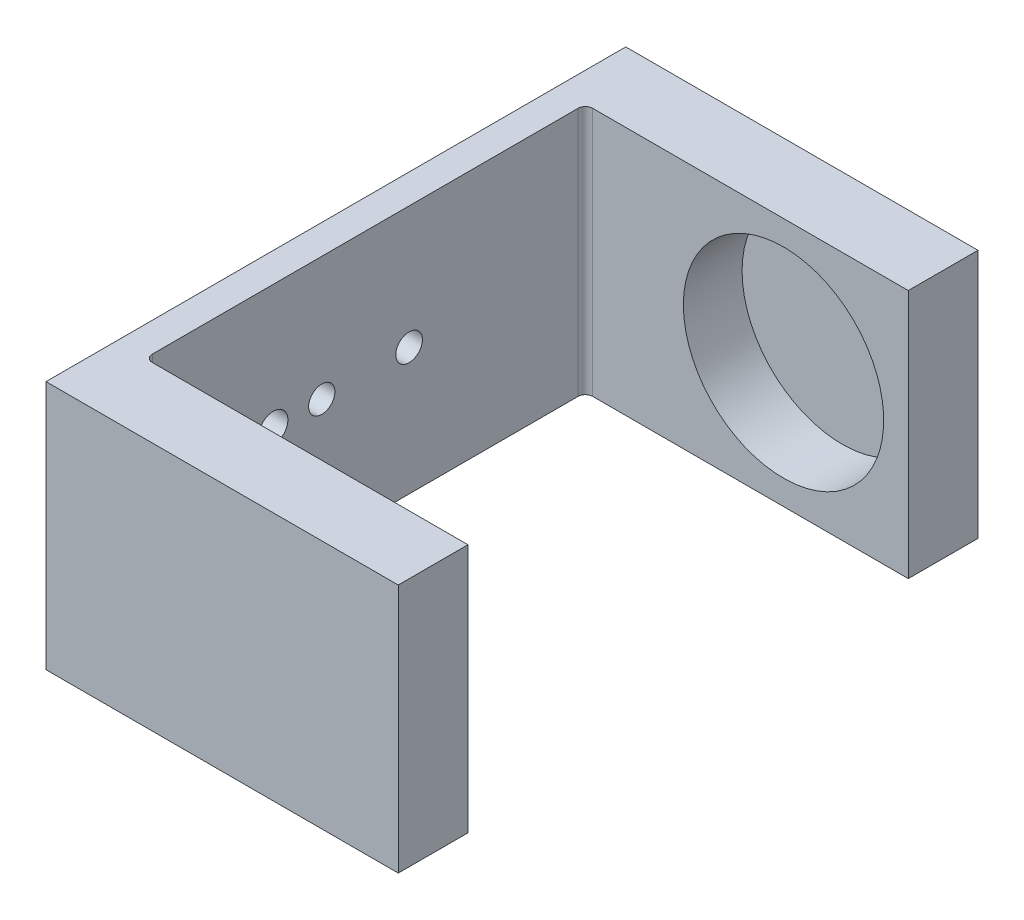
SolidWorks part; units mm, degrees
ref_plane "Front Plane" through (0, 0, 0) normal (0, 0, 1) x (1, 0, 0)
ref_plane "Top Plane" through (0, 0, 0) normal (0, 1, 0) x (1, 0, 0)
ref_plane "Right Plane" through (0, 0, 0) normal (1, 0, 0) x (0, 0, -1)
sketch "Sketch1" plane through (0, 0, 0) normal (1, 0, 0) x (0, 0, -1)
  line L0 (-32.5, 0) -> (32.5, 0) construction
  line L1 (-32.5, 17) -> (32.5, 17)
  line L2 (-32.5, 17) -> (-32.5, -17)
  line L3 (-32.5, -17) -> (32.5, -17)
  line L4 (32.5, 17) -> (32.5, -17)
  line L5 (-32.5, 17) -> (32.5, -17) construction
  line L6 (-32.5, -17) -> (32.5, 17) construction
  line L7 (0, 17) -> (0, -17) construction
  circle A3 centre (-8.4221, 0.1356) radius 1.7926
  point P0 (0, 0)
  dimension "D1" = 34
  dimension "36" = 65
extrude "Boss-Extrude1" add sketch "Sketch1" against normal blind 4
ref_plane "Plane1" through (0, 0, 32.5) normal (0, 0, 1) x (1, 0, 0)
sketch "Sketch3" plane through (0, 0, 32.5) normal (0, 0, 1) x (1, 0, 0)
  line L0 (-4, -17) -> (0, -17) construction
  line L1 (-4, 17) -> (44, 17)
  line L2 (-4, 17) -> (-4, -17)
  line L3 (-4, -17) -> (44, -17)
  line L4 (44, 17) -> (44, -17)
  line L5 (20, 17) -> (20, -17) construction
  line L6 (-4, 0) -> (44, 0) construction
  line L7 (20, 17) -> (20, -17) construction
  point P7 (-2, -17)
  dimension "D2" = 48
extrude "Boss-Extrude2" add sketch "Sketch3" along normal blind 9.5
ref_plane "Plane4" through (0, 0, 19.5) normal (0, 0, -1) x (-1, 0, 0)
ref_plane "Plane5" through (0, 0, 13.5) normal (0, 0, -1) x (-1, 0, 0)
ref_plane "Plane6" through (0, 0, 2.5) normal (0, 0, -1) x (-1, 0, 0)
mirror "Mirror1" about plane through (0, 0, 2.5) normal (0, 0, -1) of "Boss-Extrude2"
fillet "Fillet4" radius 1 1 edges at (0, 0, 32.5)
fillet "Fillet5" radius 1 1 edges at (0, 0, -27.5)
sketch "Sketch5" plane through (0, 0, 32.5) normal (0, 0, -1) x (-1, 0, 0)
  line L0 (-44, 0) -> (-1, 0) construction
  line L1 (-44, -17) -> (-44, 17) construction
  line L2 (-1, -17) -> (-1, 17) construction
  circle A0 centre (-27, 0) radius 13.65
  dimension "D1" = 27.3
  dimension "D2" = 17
extrude "Cut-Extrude1" cut sketch "Sketch5" against normal blind 8
mirror "Mirror2" about plane through (0, 0, 2.5) normal (0, 0, -1) of "Cut-Extrude1"
sketch "Sketch6" plane through (-4, 0, 0) normal (-1, 0, 0) x (0, 0, 1)
  circle A0 centre (-3.4778, 0.3145) radius 1.817
  circle A1 centre (15.0224, 0.0293) radius 1.989
extrude "Cut-Extrude2" cut sketch "Sketch6" against normal blind 10 contours A1 | A0
